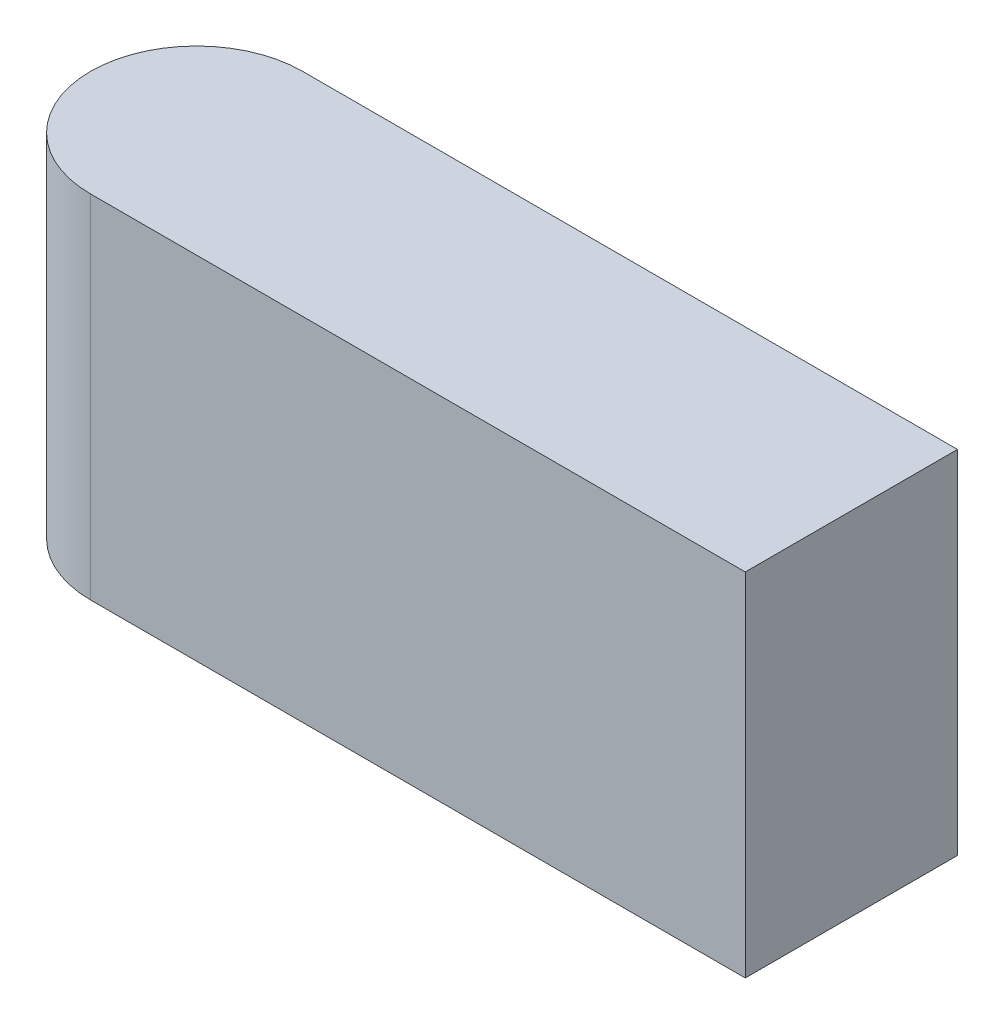
SolidWorks part; units mm, degrees
material "Copper"
ref_plane "Front Plane" through (0, 0, 0) normal (0, 0, 1) x (1, 0, 0)
ref_plane "Top Plane" through (0, 0, 0) normal (0, 1, 0) x (1, 0, 0)
ref_plane "Right Plane" through (0, 0, 0) normal (1, 0, 0) x (0, 0, -1)
sketch "Sketch1" plane through (0, 0, 0) normal (0, 1, 0) x (1, 0, 0)
  line L1 (0, 0) -> (54, 0)
  line L3 (0, 17.5) -> (54, 17.5)
  line L4 (54, 0) -> (54, 17.5)
  arc A0 (0, 0) -> (0, 17.5) centre (0, 8.75) cw
  point P6 (0, 8.75)
  point P7 (-0.533, 17.5)
  dimension "D1" = 54
  dimension "D2" = 17.5
extrude "Boss-Extrude1" add sketch "Sketch1" along normal blind 29
